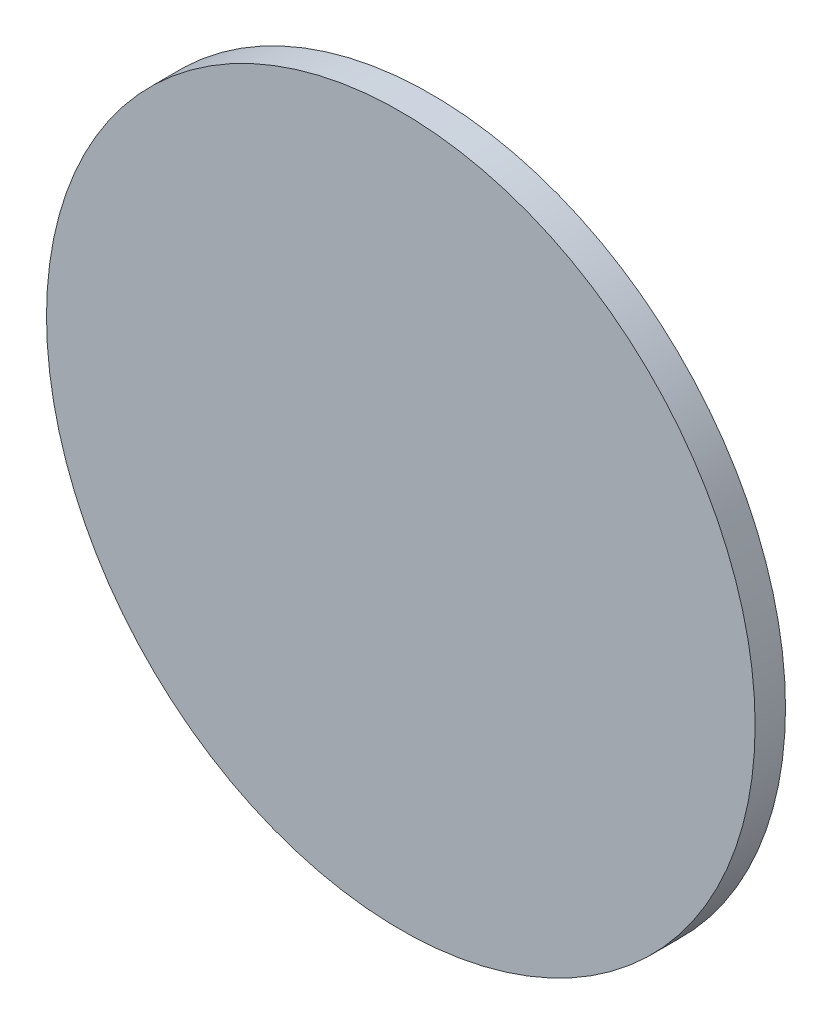
SolidWorks part; units mm, degrees
ref_plane "Front Plane" through (0, 0, 0) normal (0, 0, 1) x (1, 0, 0)
ref_plane "Top Plane" through (0, 0, 0) normal (0, 1, 0) x (1, 0, 0)
ref_plane "Right Plane" through (0, 0, 0) normal (1, 0, 0) x (0, 0, -1)
sketch "Sketch1" plane through (0, 0, 0) normal (0, 0, 1) x (1, 0, 0)
  circle A0 centre (0, 0) radius 350
  dimension "D1" = 700
extrude "Boss-Extrude1" add sketch "Sketch1" along normal blind 30
